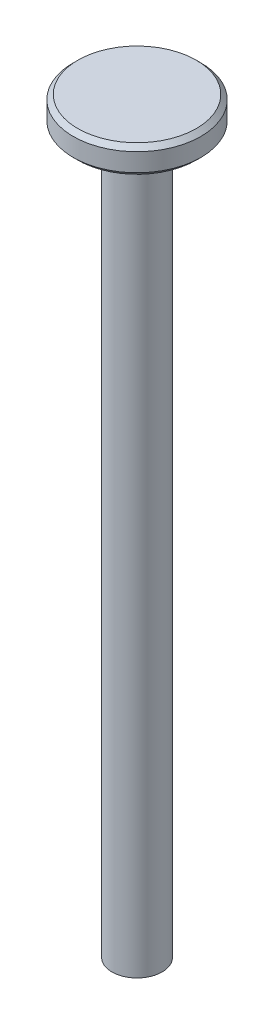
SolidWorks part; units mm, degrees
material "AISI 1015 Steel, Cold Drawn (SS)"
ref_plane "Front Plane" through (0, 0, 0) normal (0, 0, 1) x (1, 0, 0)
ref_plane "Top Plane" through (0, 0, 0) normal (0, 1, 0) x (1, 0, 0)
ref_plane "Right Plane" through (0, 0, 0) normal (1, 0, 0) x (0, 0, -1)
sketch "Sketch2" plane through (0, 0, 0) normal (0, 0, 1) x (1, 0, 0)
  line L0 (0, 0) -> (0, 79)
  line L1 (0, 79) -> (6.5, 79)
  line L2 (7, 78.5) -> (7, 76.5)
  line L3 (6.5, 76) -> (2.75, 76)
  line L4 (2.75, 76) -> (2.75, -3)
  line L5 (2.75, -3) -> (1.75, -3)
  line L8 (1.75, -3) -> (1.75, 0)
  line L9 (1.75, 0) -> (0, 0)
  line L10 (6.5, 79) -> (7, 78.5)
  line L11 (7, 76.5) -> (6.5, 76)
  line L12 (0, -28.5046) -> (0, 100.2579) construction
  point P4 (7, 79)
  point P5 (7, 76)
  dimension "D1" = 79
  dimension "D2" = 3
  dimension "D3" = 1.75
  dimension "D4" = 3
  dimension "D5" = 7
  dimension "D6" = 2.75
revolve "Revolve1" add sketch "Sketch2" angle 360 about L12
